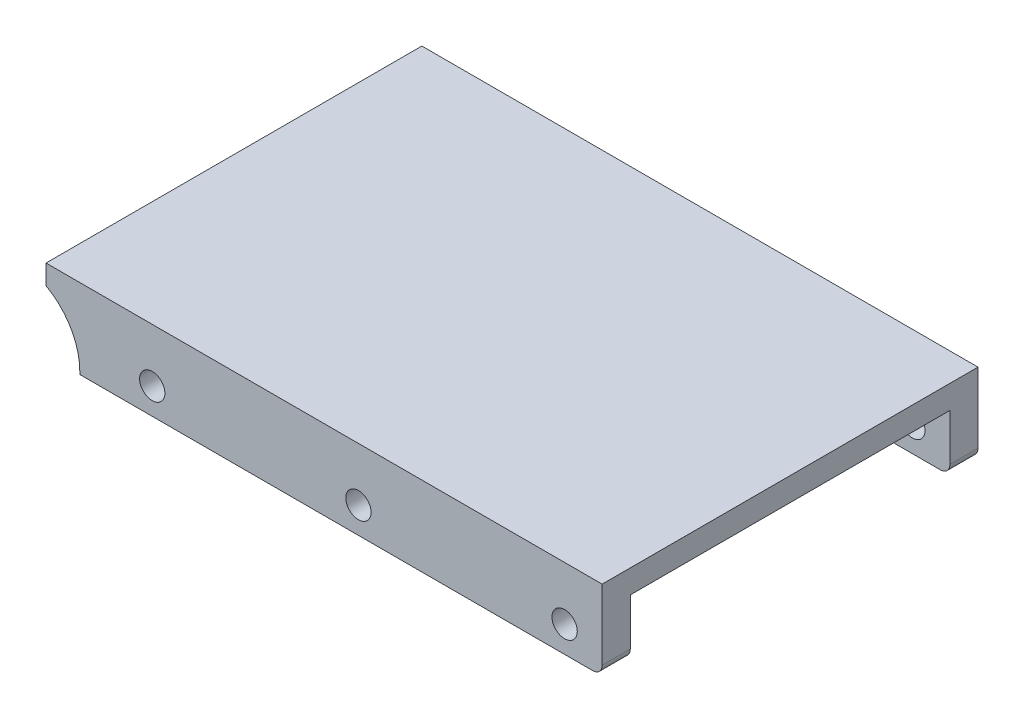
SolidWorks part; units mm, degrees
material "ABS PC"
ref_plane "Front Plane" through (0, 0, 0) normal (0, 0, 1) x (1, 0, 0)
ref_plane "Top Plane" through (0, 0, 0) normal (0, 1, 0) x (1, 0, 0)
ref_plane "Right Plane" through (0, 0, 0) normal (1, 0, 0) x (0, 0, -1)
sketch "Sketch1" plane through (0, 0, 0) normal (0, 0, 1) x (1, 0, 0)
  line L0 (0, 0) -> (0, 52.578)
  line L1 (0, 52.578) -> (6, 52.578)
  line L2 (6, 52.578) -> (6, 8.5)
  line L3 (6, 8.5) -> (76, 8.5)
  line L4 (76, 8.5) -> (76, 0)
  line L5 (76, 0) -> (0, 0)
  dimension "D1" = 52.578
  dimension "D2" = 8.5
  dimension "D3" = 6
  dimension "D4" = 76
extrude "Boss-Extrude1" add sketch "Sketch1" along normal blind 40.1
sketch "Sketch3" plane through (0, 0, 40.1) normal (0, 0, 1) x (1, 0, 0)
  line L0 (0, 52.578) -> (0, 0) construction
  line L1 (0, 0) -> (76, 0) construction
  circle A0 centre (27.996, 2.8) radius 1.35
  circle A1 centre (49.996, 2.8) radius 1.35
  circle A2 centre (71.996, 2.8) radius 1.35
  dimension "D1" = 2.7
  dimension "D4" = 2.7
  dimension "D5" = 2.7
  dimension "D2" = 27.996
  dimension "D3" = 2.8
  dimension "D6" = 22
  dimension "D7" = 22
extrude "Cut-Extrude2" cut sketch "Sketch3" against normal blind 50.8
sketch "Sketch4" plane through (0, 0, 0) normal (-1, 0, 0) x (0, 0, 1)
  line L0 (40.1, 0) -> (0, 0) construction
  line L1 (20.05, 0) -> (20.05, 52.578) construction
  line L2 (40.1, 52.578) -> (0, 52.578) construction
  line L3 (40.1, 52.578) -> (40.1, 0) construction
  line L5 (0, 52.578) -> (0, 0) construction
  circle A0 centre (27.88, 17.6) radius 1.016
  circle A1 centre (11.88, 17.6) radius 1.016
  circle A2 centre (27.88, 49.6) radius 1.016
  circle A3 centre (11.88, 49.6) radius 1.016
  dimension "D1" = 2.032
  dimension "D3" = 2.032
  dimension "D4" = 2.978
  dimension "D2" = 17.6
  dimension "D5" = 12.22
  dimension "D6" = 12.22
  dimension "D7" = 11.88
  dimension "D8" = 11.88
  dimension "D9" = 2.978
extrude "Cut-Extrude3" cut sketch "Sketch4" against normal blind 50.8
sketch "Sketch6" plane through (0, 0, 0) normal (0, -1, 0) x (1, 0, 0)
  line L0 (0, 40.1) -> (76, 40.1) construction
  line L1 (19, 37.1) -> (81.0861, 37.1)
  line L2 (19, 37.1) -> (19, 3)
  line L3 (19, 3) -> (81.0861, 3)
  line L4 (81.0861, 37.1) -> (81.0861, 3)
  line L5 (0, 0) -> (76, 0) construction
  line L6 (0, 40.1) -> (0, 0) construction
  dimension "D1" = 3
  dimension "D2" = 3
  dimension "D3" = 19
  dimension "D4" = 62.0861
extrude "Cut-Extrude4" cut sketch "Sketch6" against normal blind 6
ref_plane "Plane5" through (0, 0, 20.05) normal (0, 0, -1) x (-1, 0, 0)
sketch "Sketch16" plane through (0, 0, 40.1) normal (0, 0, 1) x (1, 0, 0)
  line L0 (6, 8.5) -> (26, 8.5)
  line L1 (76, 8.5) -> (6, 8.5) construction
  line L2 (26, 8.5) -> (6, 33.5)
  line L3 (6, 8.5) -> (6, 52.578) construction
  line L4 (6, 33.5) -> (6, 8.5)
  dimension "D1" = 20
  dimension "D2" = 25
extrude "Boss-Extrude5" add sketch "Sketch16" against normal blind 2
mirror "Mirror2" about plane through (0, 0, 20.05) normal (0, 0, -1) of "Boss-Extrude5"
fillet "Fillet1" radius 1 5 edges at (3, 52.578, 0) (3, 52.578, 40.1) (0, 0, 20.05) (76, 0, 1.5) (76, 0, 38.6)
sketch "Sketch17" plane through (0, 0, 40.1) normal (0, 0, 1) x (1, 0, 0)
  line L0 (0, 51.578) -> (0, 1) construction
  line L1 (0, 8.5) -> (87.9721, 8.5)
  line L2 (0, 8.5) -> (0, 70.8924)
  line L3 (0, 70.8924) -> (87.9721, 70.8924)
  line L4 (87.9721, 8.5) -> (87.9721, 70.8924)
extrude "Cut-Extrude5" cut sketch "Sketch17" against normal through all
sketch "Sketch18" plane through (0, 0, 40.1) normal (0, 0, 1) x (1, 0, 0)
  line L0 (1, 0) -> (75, 0) construction
  line L1 (0, 8.5) -> (11.938, 8.5)
  line L2 (0, 8.5) -> (0, 0)
  line L3 (0, 0) -> (11.938, 0)
  line L4 (11.938, 8.5) -> (11.938, 0)
  dimension "D1" = 11.938
extrude "Cut-Extrude6" cut sketch "Sketch18" against normal through all
sketch "Sketch19" plane through (0, 0, 40.1) normal (0, 0, 1) x (1, 0, 0)
  line L0 (11.938, 7.1005) -> (21.4919, 7.1005)
  line L1 (11.938, 0) -> (11.938, 8.5) construction
  line L2 (21.4919, 7.1005) -> (21.4919, 0)
  line L3 (11.938, 0) -> (75, 0) construction
  line L4 (21.4919, 0) -> (11.938, 0)
  line L5 (11.938, 0) -> (11.938, 7.1005)
extrude "Boss-Extrude6" add sketch "Sketch19" against normal blind 40
sketch "Sketch20" plane through (0, 0, 40.1) normal (0, 0, 1) x (1, 0, 0)
  line L0 (11.938, 7.274) -> (20.2703, 7.274)
  line L1 (11.938, 0) -> (11.938, 8.5) construction
  line L2 (20.2703, 7.274) -> (20.2703, 0)
  line L3 (11.938, 0) -> (75, 0) construction
  line L4 (11.938, 7.274) -> (11.938, 0)
  line L5 (11.938, 0) -> (20.2703, 0)
extrude "Cut-Extrude8" cut sketch "Sketch20" against normal through all
fillet "Fillet2" radius 7 1 edges at (20.2703, 7.274, 20.05)
sketch "Sketch21" plane through (0, 0, 40.1) normal (0, 0, 1) x (1, 0, 0)
  line L1 (11.938, 8.5) -> (16.6624, 8.5)
  line L2 (11.938, 8.5) -> (11.938, -1.5)
  line L3 (11.938, -1.5) -> (16.6624, -1.5)
  line L4 (16.6624, 8.5) -> (16.6624, -1.5)
  dimension "D1" = 10
  dimension "D2" = 4.7244
extrude "Cut-Extrude9" cut sketch "Sketch21" against normal through all
sketch "Sketch22" plane through (21.4919, 0, 0) normal (1, 0, 0) x (0, 0, -1)
  line L4 (-37.1, 6) -> (-37.1, 0)
  line L5 (-37.1, 0) -> (-3, 0)
  line L6 (-3, 0) -> (-3, 6)
  line L7 (-3, 6) -> (-37.1, 6)
  line L8 (-37.1, 6) -> (-37.1, 0)
  line L9 (-37.1, 0) -> (-3, 0)
  line L10 (-3, 0) -> (-3, 6)
  line L11 (-3, 6) -> (-37.1, 6)
  dimension "D1" = 0
extrude "Cut-Extrude10" cut sketch "Sketch22" against normal through all
